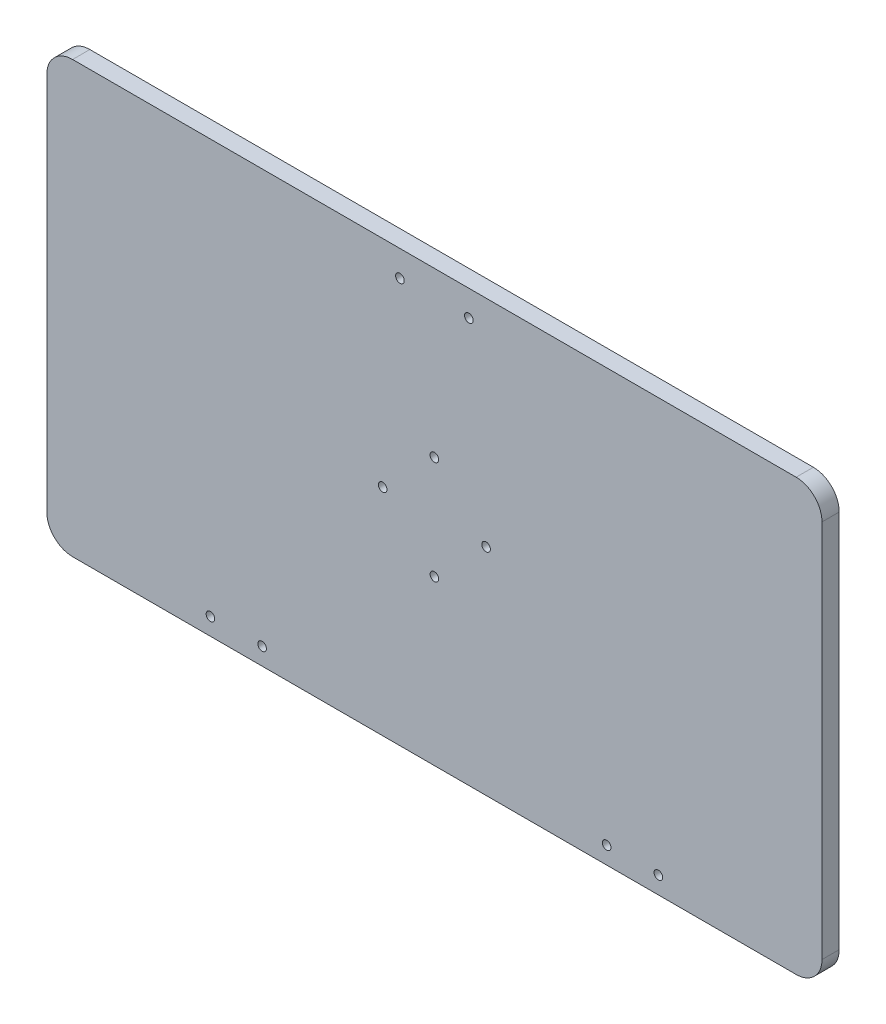
SolidWorks part; units mm, degrees
ref_plane "Alzado" through (0, 0, 0) normal (0, 0, 1) x (1, 0, 0)
ref_plane "Planta" through (0, 0, 0) normal (0, 1, 0) x (1, 0, 0)
ref_plane "Vista lateral" through (0, 0, 0) normal (1, 0, 0) x (0, 0, -1)
sketch "Croquis1" plane through (0, 0, 0) normal (0, 0, 1) x (1, 0, 0)
  line L0 (415, 125) -> (450, 125) construction
  line L1 (15, 0) -> (435, 0)
  line L2 (0, 15) -> (0, 235)
  line L3 (15, 250) -> (435, 250)
  line L4 (450, 15) -> (450, 235)
  line L9 (110, 250) -> (110, 0) construction
  line L16 (225, 250) -> (225, 0) construction
  line L17 (0, 125) -> (450, 125) construction
  line L18 (205, 235) -> (245, 235) construction
  line L66 (315, 10) -> (325, 10) construction
  line L67 (315, 0) -> (365, 0) construction
  line L68 (315, 0) -> (315, 20) construction
  line L69 (315, 20) -> (365, 20) construction
  line L70 (365, 0) -> (365, 20) construction
  line L71 (355, 10) -> (365, 10) construction
  line L72 (325, 10) -> (355, 10) construction
  line L73 (340, 10) -> (340, 20) construction
  arc A5 (435, 250) -> (450, 235) centre (435, 235) cw
  arc A6 (435, 0) -> (450, 15) centre (435, 15) ccw
  arc A7 (15, 0) -> (0, 15) centre (15, 15) cw
  arc A8 (0, 235) -> (15, 250) centre (15, 235) cw
  circle A13 centre (205, 235) radius 2.5
  circle A14 centre (245, 235) radius 2.5
  circle A20 centre (325, 10) radius 2.5
  circle A21 centre (355, 10) radius 2.5
  circle A24 centre (95, 10) radius 2.5
  circle A25 centre (125, 10) radius 2.5
  circle A28 centre (255, 125) radius 2.5
  circle A29 centre (225, 95) radius 2.5
  circle A30 centre (195, 125) radius 2.5
  circle A31 centre (225, 155) radius 2.5
  point P29 (450, 0)
  point P32 (0, 0)
  point P35 (0, 250)
  point P46 (225, 125)
  point P53 (225, 235)
  dimension "D5" = 4
  dimension "D10" = 15
  dimension "D11" = 30
  dimension "D18" = 5
  dimension "D13" = 5
  dimension "D3" = 5
  dimension "D1" = 450
  dimension "D2" = 250
  dimension "D4" = 30
  dimension "D6" = 110
  dimension "D12" = 50
  dimension "D15" = 90
  dimension "D16" = 20
  dimension "D19" = 40
  dimension "D27" = 15
extrude "Saliente-Extruir1" add sketch "Croquis1" along normal blind 10
